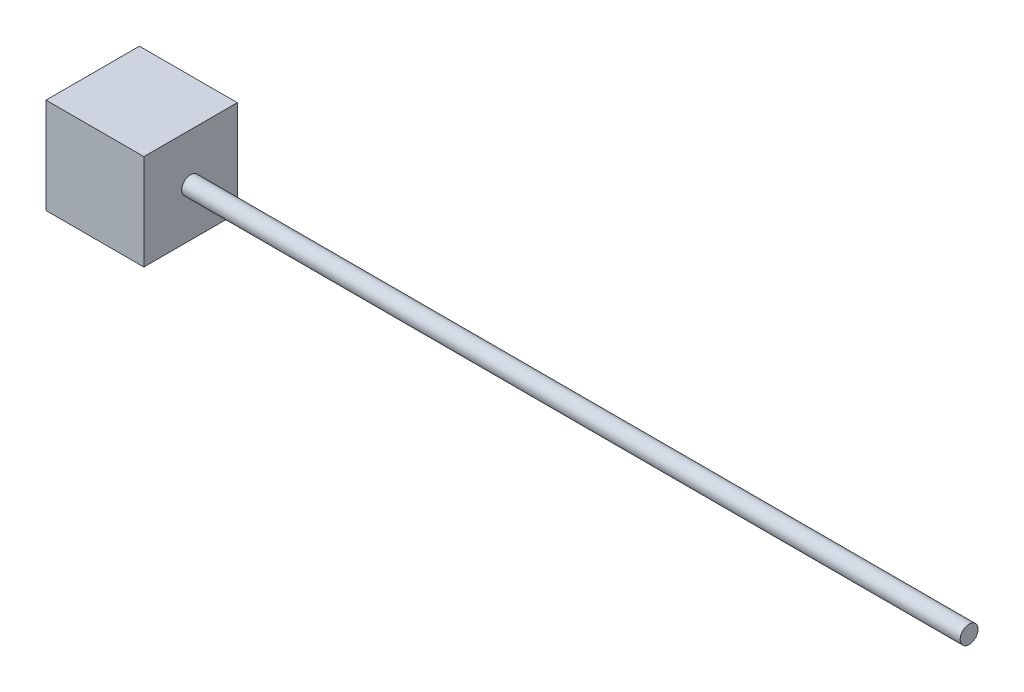
SolidWorks part; units mm, degrees
ref_plane "Alzado" through (0, 0, 0) normal (0, 0, 1) x (1, 0, 0)
ref_plane "Planta" through (0, 0, 0) normal (0, 1, 0) x (1, 0, 0)
ref_plane "Vista lateral" through (0, 0, 0) normal (1, 0, 0) x (0, 0, -1)
sketch "Croquis1" plane through (0, 0, 0) normal (0, 1, 0) x (1, 0, 0)
  line L1 (-22, 21) -> (22, 21)
  line L2 (-22, 21) -> (-22, -21)
  line L3 (-22, -21) -> (22, -21)
  line L4 (22, 21) -> (22, -21)
  line L5 (-22, 21) -> (22, -21) construction
  line L6 (-22, -21) -> (22, 21) construction
  point P0 (0, 0)
  dimension "D1" = 44
  dimension "D2" = 42
extrude "Saliente-Extruir1" add sketch "Croquis1" along normal mid plane 43
sketch "Croquis2" plane through (22, 0, 0) normal (1, 0, 0) x (0, 0, -1)
  circle A0 centre (0, 0) radius 4
  dimension "D1" = 8
extrude "Saliente-Extruir2" add sketch "Croquis2" along normal blind 350
